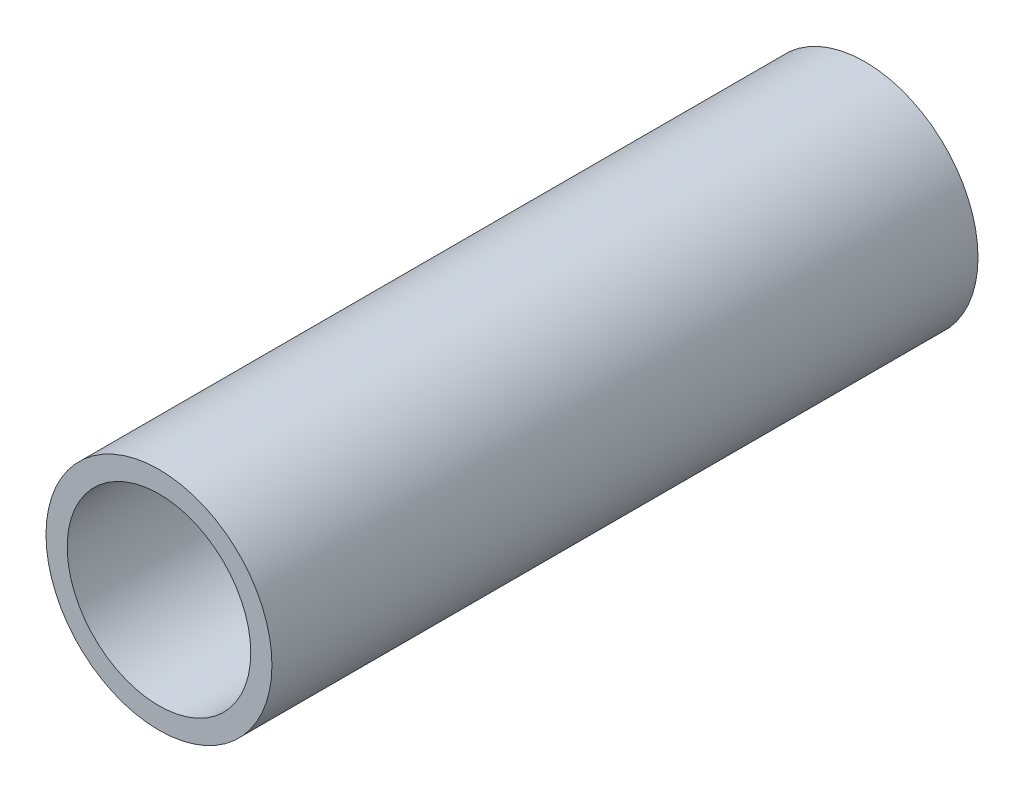
SolidWorks part; units mm, degrees
ref_plane "Plan de face" through (0, 0, 0) normal (0, 0, 1) x (1, 0, 0)
ref_plane "Plan de dessus" through (0, 0, 0) normal (0, 1, 0) x (1, 0, 0)
ref_plane "Plan de droite" through (0, 0, 0) normal (1, 0, 0) x (0, 0, -1)
sketch "Esquisse1" plane through (0, 0, 0) normal (0, 0, 1) x (1, 0, 0)
  circle A0 centre (0, 0) radius 6.5
  circle A1 centre (0, 0) radius 8
  dimension "D1" = 13
  dimension "D2" = 16
extrude "Boss.-Extru.1" add sketch "Esquisse1" along normal blind 50
